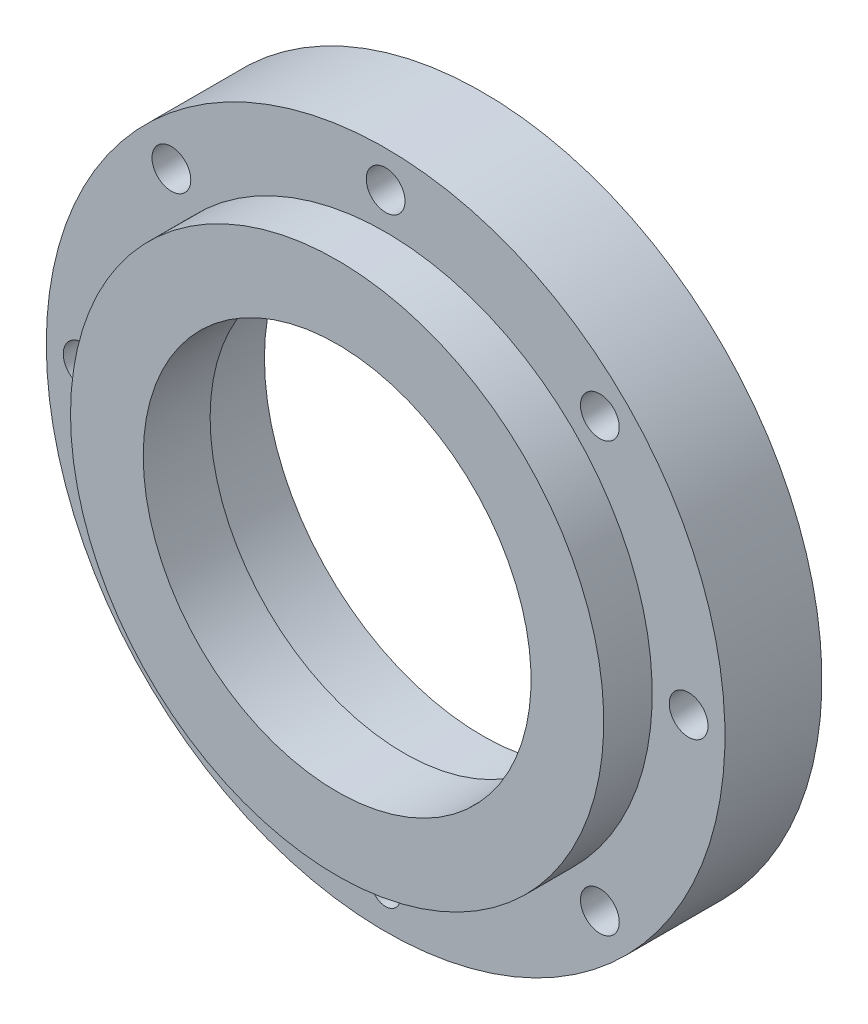
SolidWorks part; units mm, degrees
ref_plane "Front Plane" through (0, 0, 0) normal (0, 0, 1) x (1, 0, 0)
ref_plane "Top Plane" through (0, 0, 0) normal (0, 1, 0) x (1, 0, 0)
ref_plane "Right Plane" through (0, 0, 0) normal (1, 0, 0) x (0, 0, -1)
sketch "Sketch1" plane through (0, 0, 0) normal (0, 1, 0) x (1, 0, 0)
  line L0 (-55, -19.7958) -> (-55, -9.7958)
  line L1 (-55, -9.7958) -> (-55, -68.7958) construction
  line L2 (-55, -9.7958) -> (-70, -9.7958)
  line L3 (-55, -19.7958) -> (-40, -19.7958)
  line L4 (-40, -19.7958) -> (-40, -6)
  line L5 (-40, -6) -> (-45, -6)
  line L6 (-45, -6) -> (-45, 10.2042)
  line L7 (-45, 10.2042) -> (-70, 10.2042)
  line L8 (-70, 10.2042) -> (-70, -9.7958)
  line L9 (-70, -9.7958) -> (-70, -84.7958) construction
  line L10 (-45, -6) -> (45, -6) construction
  line L11 (-45, 6) -> (-45, -6) construction
  line L12 (0, 52.7074) -> (0, -119.6493) construction
  dimension "D1" = 15
  dimension "D2" = 10
  dimension "D3" = 20
revolve "Revolve1" add sketch "Sketch1" angle 360 about L12
sketch "Sketch2" plane through (0, 0, 9.7958) normal (0, 0, 1) x (1, 0, 0)
  line L0 (0, 62.5) -> (0, -62.5) construction
  circle A0 centre (0, 0) radius 62.5 construction
  circle A2 centre (0, -62.5) radius 3
  dimension "D1" = 125
  dimension "D3" = 6
extrude "Cut-Extrude1" cut sketch "Sketch2" against normal blind 9 contours A2
sketch "Sketch3" plane through (0, 0, 9.7958) normal (0, 0, 1) x (1, 0, 0)
  line L0 (0, 0) -> (0, 62.5) construction
  circle A0 centre (0, 62.5) radius 4
  dimension "D2" = 8
  dimension "D1" = 62.5
extrude "Cut-Extrude2" cut sketch "Sketch3" against normal blind 10
sketch "Sketch4" plane through (0, 0, 9.7958) normal (0, 0, 1) x (1, 0, 0)
  line L0 (0, 70) -> (0, -70) construction
  line L1 (-62.5, 0) -> (62.5, 0) construction
  line L2 (0, 0) -> (44.1942, 44.1942) construction
  line L3 (0, 0) -> (44.1942, -44.1942) construction
  line L4 (0, 0) -> (-44.1942, -44.1942) construction
  line L5 (0, 0) -> (-44.1942, 44.1942) construction
  circle A0 centre (0, 0) radius 70 construction
  circle A2 centre (0, 0) radius 62.5 construction
  dimension "D3" = 125
  dimension "D1" = 45
  dimension "D2" = 45
hole_wizard "Ø8.0mm Dowel Hole1" positions "Sketch5" profile "Sketch6" hole size "Ø8.0" standard "ANSI Metric" end condition through all
sketch "Sketch5" plane through (0, 0, 9.7958) normal (0, 0, 1) x (1, 0, 0)
  point P0 (44.1942, 44.1942)
  point P3 (62.5, 0)
  point P6 (44.1942, -44.1942)
  point P9 (-44.1942, -44.1942)
  point P12 (-62.5, 0)
  point P15 (-44.1942, 44.1942)
sketch "Sketch6" plane through (44.1942, 44.1942, 9.7958) normal (1, 0, 0) x (0, -1, 0)
  line L0 (0, 0) -> (0, 20)
  line L1 (0, 20) -> (4, 20)
  line L2 (4, 20) -> (4, 0)
  line L5 (4, 0) -> (0, 0)
  line L11 (0, -6.35) -> (0, 107.95) construction
  dimension "Thru Hole Dia." = 8
  dimension "Thru Hole Depth" = 20
